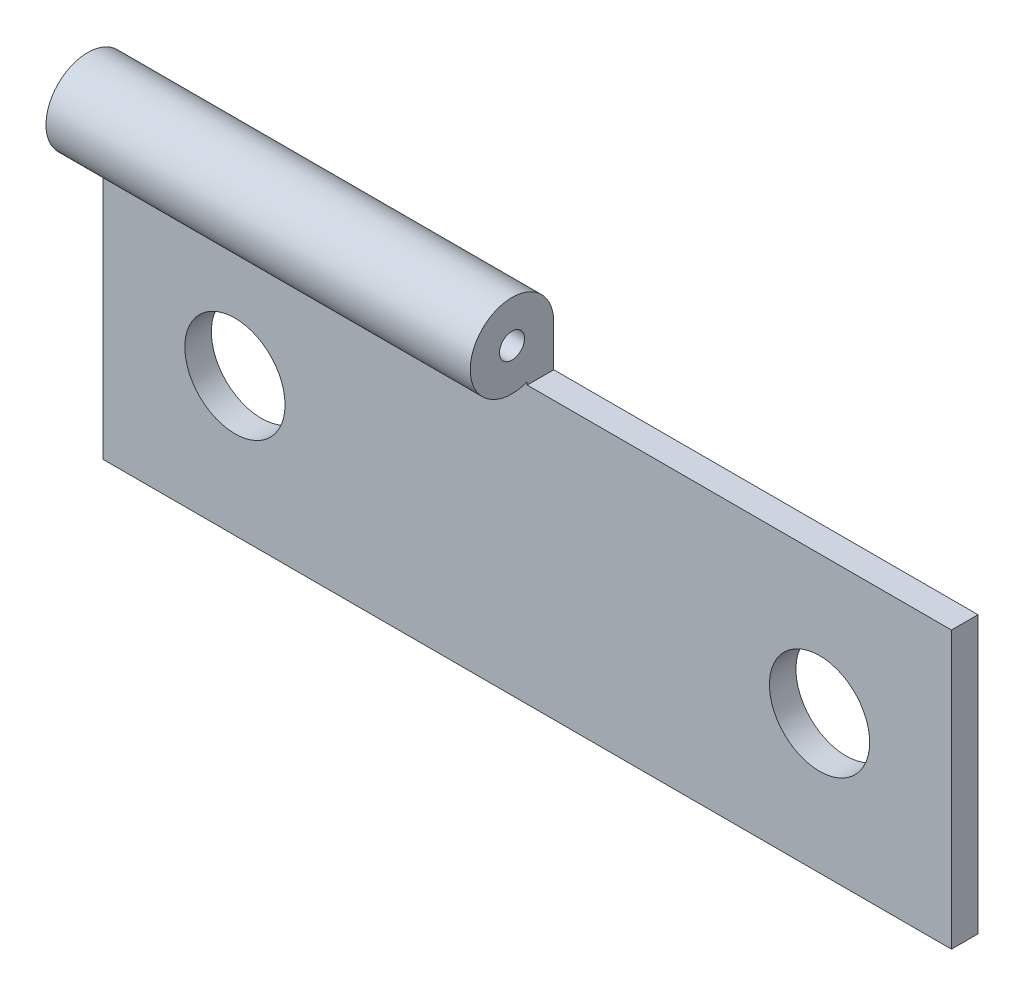
SolidWorks part; units mm, degrees
ref_plane "Alzado" through (0, 0, 0) normal (0, 0, 1) x (1, 0, 0)
ref_plane "Planta" through (0, 0, 0) normal (0, 1, 0) x (1, 0, 0)
ref_plane "Vista lateral" through (0, 0, 0) normal (1, 0, 0) x (0, 0, -1)
sketch "Sketch1" plane through (0, 0, 0) normal (0, 0, 1) x (1, 0, 0)
  line L0 (-25.4, 0) -> (25.4, 0)
  line L2 (25.4, 0) -> (25.4, 19.05)
  line L3 (25.4, 19.05) -> (-25.4, 19.05)
  line L4 (-25.4, 0) -> (-25.4, 19.05)
  line L5 (0, 0) -> (-25.4, 19.05) construction
  line L6 (25.4, 19.05) -> (0, 0) construction
  point P0 (0, 0)
  dimension "D1" = 50.8
  dimension "D2" = 19.05
  dimension "D3" = 25.4
extrude "Boss-Extrude1" add sketch "Sketch1" along normal blind 1.5875
sketch "Sketch2" plane through (-25.4, 0, 0) normal (-1, 0, 0) x (0, 0, 1)
  circle A0 centre (2.5, 19.05) radius 0.75
  circle A2 centre (2.5, 19.05) radius 2.5
  point P4 (2.4952, 18.9812)
  point P6 (2.5, 19.05)
  dimension "D1" = 1.5
  dimension "D2" = 5
extrude "Boss-Extrude2" add sketch "Sketch2" against normal blind 25.4
sketch "Sketch3" plane through (0, 0, 0) normal (1, 0, 0) x (0, 0, -1)
  line L0 (-2.5, 16.55) -> (0, 16.55)
  line L1 (0, 0) -> (0, 19.05) construction
  line L2 (0, 16.55) -> (0, 19.05)
  arc A0 (0, 19.05) -> (-2.5, 16.55) centre (-2.5, 19.05) ccw
  arc A1 (0, 19.05) -> (-1.5875, 16.7225) centre (-2.5, 19.05) ccw construction
extrude "Cut-Extrude2" cut sketch "Sketch3" along normal up to surface (25.4 mm away) up to face at (25.4, 9.525, 0.7937)
hole_wizard "Ø6.0 mm Dowel Holes1" positions "Sketch4" profile "Sketch5" hole size "Ø6.0" standard "ANSI Metric"
sketch "Sketch4" plane through (0, 0, 1.5875) normal (0, 0, 1) x (1, 0, 0)
  line L0 (25.4, 0) -> (25.4, 16.55) construction
  point P0 (-17.5, 8.275)
  point P2 (17.5, 8.275)
  point P9 (0, 0)
  point P10 (25.4, 8.275)
  point P11 (0, 0)
  dimension "D1" = 35
  dimension "D2" = 17.5
sketch "Sketch5" plane through (-17.5, 8.275, 1.5875) normal (1, 0, 0) x (0, -1, 0)
  line L0 (0, 0) -> (0, 31.8026)
  line L1 (0, 31.8026) -> (3, 30)
  line L2 (3, 30) -> (3, 0)
  line L5 (3, 0) -> (0, 0)
  line L10 (0, 31.8026) -> (-3, 30) construction
  line L11 (0, -6.35) -> (0, 107.95) construction
  dimension "Hole Dia." = 6
  dimension "Hole Depth" = 30
  dimension "Drill Angle" = 118
